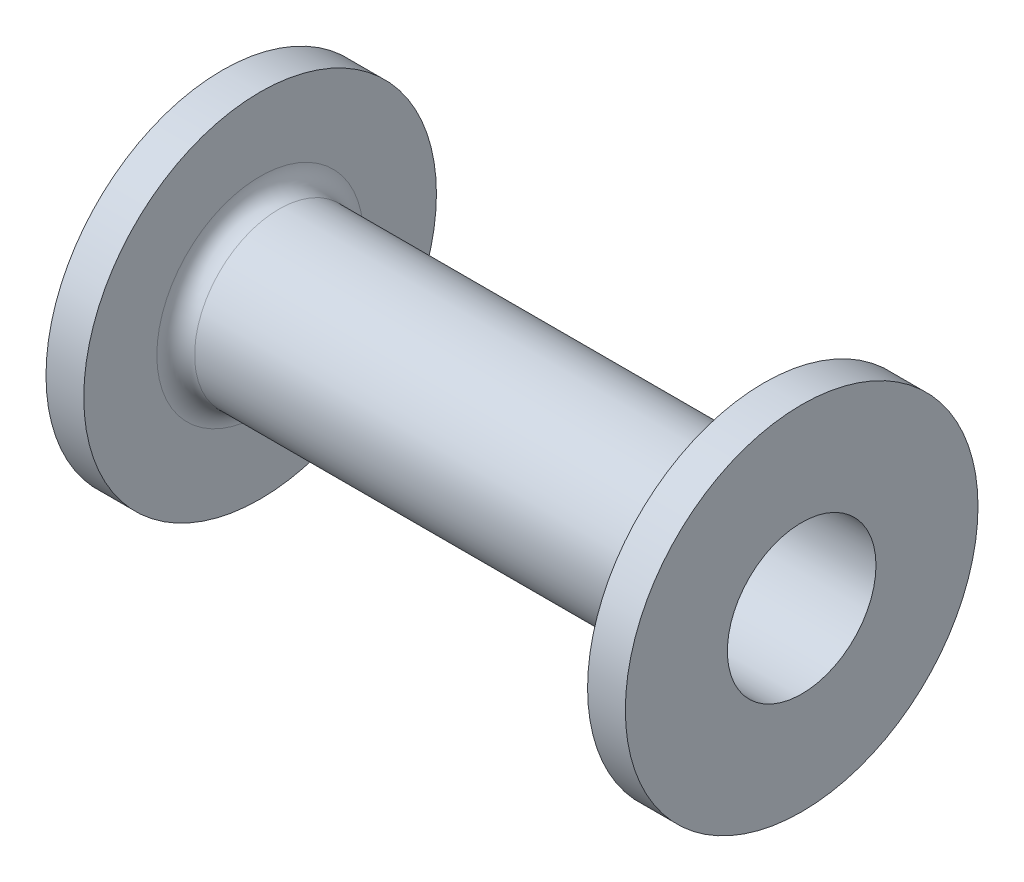
SolidWorks part; units mm, degrees
ref_plane "Front Plane" through (0, 0, 0) normal (0, 0, 1) x (1, 0, 0)
ref_plane "Top Plane" through (0, 0, 0) normal (0, 1, 0) x (1, 0, 0)
ref_plane "Right Plane" through (0, 0, 0) normal (1, 0, 0) x (0, 0, -1)
sketch "Sketch1" plane through (0, 0, 0) normal (0, 0, 1) x (1, 0, 0)
  line L0 (0, 5.9) -> (0, 14)
  line L1 (0, 0) -> (-13.4865, 0) construction
  line L2 (0, 14) -> (3, 14)
  line L3 (3, 14) -> (3, 8.2)
  line L4 (3, 5.9) -> (43, 5.9)
  line L5 (4.5, 6.7) -> (41.5, 6.7)
  line L6 (3, 5.9) -> (0, 5.9)
  line L7 (43, 8.2) -> (43, 14)
  line L8 (43, 14) -> (46, 14)
  line L9 (46, 14) -> (46, 5.9)
  line L10 (46, 5.9) -> (43, 5.9)
  arc A0 (41.5, 6.7) -> (43, 8.2) centre (41.5, 8.2) ccw
  arc A1 (4.5, 6.7) -> (3, 8.2) centre (4.5, 8.2) cw
  point P17 (3, 6.7)
  dimension "D1" = 11.8
  dimension "D2" = 3
  dimension "D6" = 1.5
  dimension "D3" = 28
  dimension "D4" = 0.8
  dimension "D5" = 40
revolve "Revolve1" add sketch "Sketch1" angle 360 about L1
